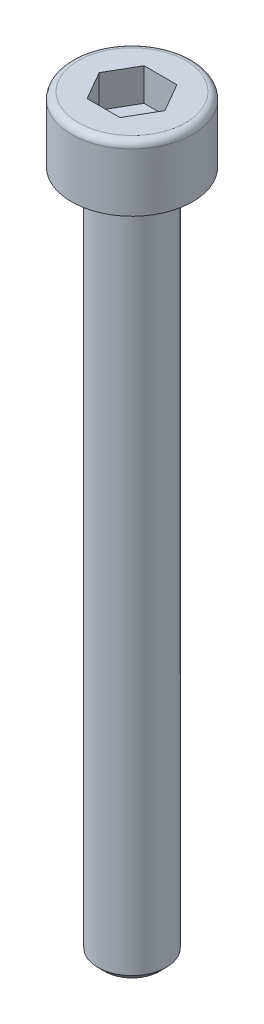
SolidWorks part; units mm, degrees
material "Cast Stainless Steel"
ref_plane "Front Plane" through (0, 0, 0) normal (0, 0, 1) x (1, 0, 0)
ref_plane "Top Plane" through (0, 0, 0) normal (0, 1, 0) x (1, 0, 0)
ref_plane "Right Plane" through (0, 0, 0) normal (1, 0, 0) x (0, 0, -1)
sketch "Sketch1" plane through (0, 0, 0) normal (0, 0, 1) x (1, 0, 0)
  line L0 (0, 0) -> (0, 2.86)
  line L1 (0, 2.86) -> (2.66, 2.86)
  line L2 (2.66, 2.86) -> (2.66, 0)
  line L3 (2.66, 0) -> (1.5, 0)
  line L4 (1.5, 0) -> (1.5, -30)
  line L5 (1.5, -30) -> (0, -30)
  line L6 (0, -30) -> (0, 0)
  line L7 (0, 2.86) -> (0, 12.7536) construction
  dimension "D1" = 30
  dimension "D2" = 2.86
  dimension "D3" = 3
  dimension "D4" = 5.32
revolve "Revolve1" add sketch "Sketch1" angle 360 about L7
chamfer "Chamfer1" distance 0.3 angle 45 1 edges at (0, -30, -1.5)
fillet "Fillet1" radius 0.3 1 edges at (0, 2.86, -2.66)
sketch "Sketch2" plane through (0, 2.86, 0) normal (0, 1, 0) x (1, 0, 0)
  line L1 (0.7217, -1.25) -> (1.4434, 0)
  line L2 (1.4434, 0) -> (0.7217, 1.25)
  line L3 (0.7217, 1.25) -> (-0.7217, 1.25)
  line L4 (-0.7217, 1.25) -> (-1.4434, 0)
  line L5 (-1.4434, 0) -> (-0.7217, -1.25)
  line L6 (-0.7217, -1.25) -> (0.7217, -1.25)
  circle A0 centre (0, 0) radius 1.25 construction
  dimension "D1" = 2.5
extrude "Cut-Extrude1" cut sketch "Sketch2" against normal blind 1.43
equation "\"d\"= 3"
equation "\"dk\"= 5.32"
equation "\"k\"= 2.86"
equation "\"s\"= 2.5"
equation "\"L\"= 30"
equation "\"D4@Sketch1\"=\"dk\""
equation "\"D2@Sketch1\"=\"k\""
equation "\"D1@Sketch1\"=\"L\""
equation "\"D3@Sketch1\"=\"d\""
equation "\"D1@Chamfer1\"=\"d\"/10"
equation "\"D1@Fillet1\"=\"d\"/10"
equation "\"D1@Sketch2\"=\"s\""
equation "\"D1@Cut-Extrude1\"=\"k\"/2"
